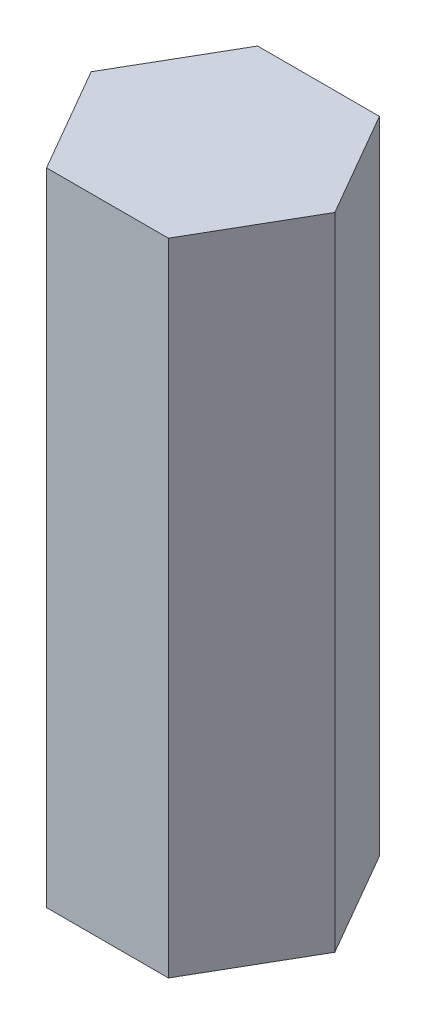
SolidWorks part; units mm, degrees
material "Pine"
ref_plane "Front Plane" through (0, 0, 0) normal (0, 0, 1) x (1, 0, 0)
ref_plane "Top Plane" through (0, 0, 0) normal (0, 1, 0) x (1, 0, 0)
ref_plane "Right Plane" through (0, 0, 0) normal (1, 0, 0) x (0, 0, -1)
sketch "Sketch1" plane through (0, 0, 0) normal (0, 1, 0) x (1, 0, 0)
  line L13 (14.6647, 0) -> (7.3323, 12.7)
  line L14 (7.3323, 12.7) -> (-7.3323, 12.7)
  line L15 (-7.3323, 12.7) -> (-14.6647, 0)
  line L16 (-14.6647, 0) -> (-7.3323, -12.7)
  line L17 (-7.3323, -12.7) -> (7.3323, -12.7)
  line L18 (7.3323, -12.7) -> (14.6647, 0)
  circle A0 centre (0, 0) radius 12.7 construction
  dimension "D1" = 25.4
extrude "Boss-Extrude2" add sketch "Sketch1" along normal blind 77.1144
